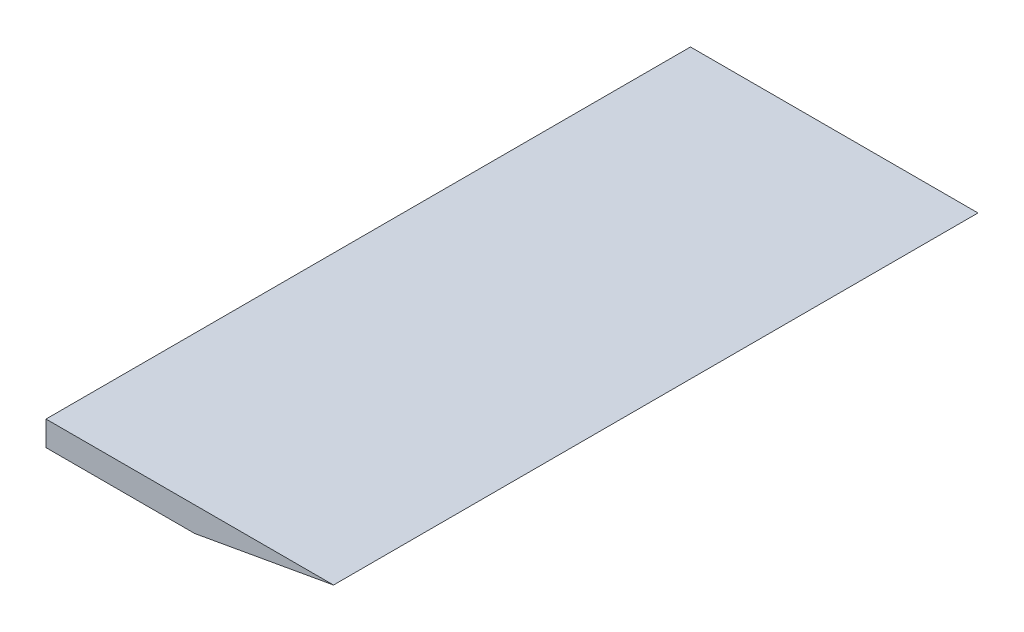
SolidWorks part; units mm, degrees
ref_plane "Front Plane" through (0, 0, 0) normal (0, 0, 1) x (1, 0, 0)
ref_plane "Top Plane" through (0, 0, 0) normal (0, 1, 0) x (1, 0, 0)
ref_plane "Right Plane" through (0, 0, 0) normal (1, 0, 0) x (0, 0, -1)
sketch "Sketch1" plane through (0, 0, 0) normal (0, 0, 1) x (1, 0, 0)
  line L0 (0, 0) -> (58, 0)
  line L1 (58, 0) -> (30, -5)
  line L2 (30, -5) -> (0, -5)
  line L3 (0, -5) -> (0, 0)
  dimension "D1" = 5
  dimension "D2" = 28
  dimension "D3" = 30
extrude "Boss-Extrude1" add sketch "Sketch1" along normal blind 130
